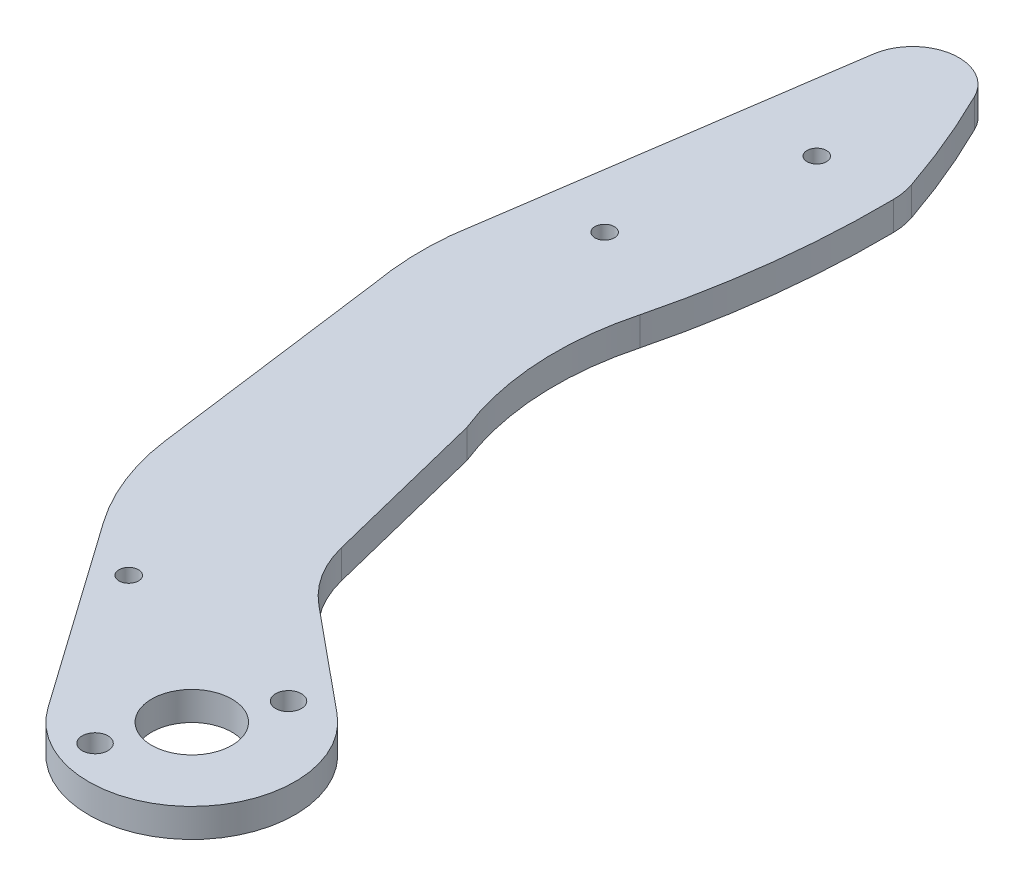
SolidWorks part; units mm, degrees
ref_plane "Front Plane" through (0, 0, 0) normal (0, 0, 1) x (1, 0, 0)
ref_plane "Top Plane" through (0, 0, 0) normal (0, 1, 0) x (1, 0, 0)
ref_plane "Right Plane" through (0, 0, 0) normal (1, 0, 0) x (0, 0, -1)
sketch "Sketch1" plane through (0, 0, 0) normal (0, 1, 0) x (1, 0, 0)
  line L42 (11.4465, 13.8917) -> (-6.607, 28.7674)
  line L43 (-13.2989, 39.3817) -> (-20.5302, 68.4972)
  line L44 (-41.4826, 160.3656) -> (-50.9327, 96.0562)
  line L45 (-50.3835, 82.3644) -> (-44.8193, 40.2497)
  line L46 (-37.8507, 22.4331) -> (-14.709, -10.3752)
  arc A148 (-22.4566, 100.5997) -> (-20.5302, 68.4972) centre (26.9938, 87.458) ccw
  arc A149 (-22.4566, 100.5997) -> (-17.768, 140.1479) centre (-171.2572, 138.2924) ccw
  arc A150 (-17.768, 140.1479) -> (-18.4178, 143.9365) centre (-30, 140) ccw
  arc A151 (-18.4178, 143.9365) -> (-26.2563, 162.7822) centre (-163.7532, 94.5401) ccw
  arc A152 (-26.2563, 162.7822) -> (-41.4826, 160.3656) centre (-33.4913, 159.1913) ccw
  arc A153 (-50.9327, 96.0562) -> (-50.3835, 82.3644) centre (0.0072, 91.2427) ccw
  circle A154 centre (0, 0) radius 7
  arc A155 (11.4465, 13.8917) -> (-14.709, -10.3752) centre (0, 0) cw
  arc A156 (-6.607, 28.7674) -> (-13.2989, 39.3817) centre (6.1114, 44.2025) cw
  arc A157 (-44.8193, 40.2497) -> (-37.8507, 22.4331) centre (-5.1639, 45.489) ccw
  circle A158 centre (-27.6733, 16.679) radius 1.7
  point P7 (-11.7063, 32.9691)
  point P11 (-43.529, 30.4833)
  dimension "D3" = 65
  dimension "D4" = 14
  dimension "D5" = 11
  dimension "D8" = 20
  dimension "D10" = 40
  dimension "D11" = 3.4
  dimension "D1" = 140
  dimension "D2" = 30
  dimension "D6" = 50
  dimension "D7" = 30
  dimension "D9" = 30
  dimension "D12" = 5
  dimension "D13" = 30
extrude "Boss-Extrude2" add sketch "Sketch1" along normal blind 5
sketch "Sketch2" plane through (0, 5, 0) normal (0, 1, 0) x (1, 0, 0)
  line L0 (11.4465, 13.8917) -> (-6.607, 28.7674) construction
  point P0 (8.4963, 16.3225)
sketch "Sketch3" plane through (0, 5, 0) normal (0, 1, 0) x (1, 0, 0)
  circle A0 centre (-31, 140) radius 1.7
  circle A1 centre (-38, 110) radius 1.7
  dimension "D1" = 3.4
  dimension "D2" = 3.4
  dimension "D3" = 30
  dimension "D4" = 110
  dimension "D5" = 38
  dimension "D6" = 7
extrude "Cut-Extrude1" cut sketch "Sketch3" against normal up to next
sketch "Sketch4" plane through (0, 5, 0) normal (0, 1, 0) x (1, 0, 0)
  point P0 (5.2512, 11.6184)
  point P1 (-5.2512, -11.6184)
hole_wizard "M4 Clearance Hole1" positions "3DSketch2" profile "Sketch6" hole size "M4" standard "ISO"
sketch3d "3DSketch2"
  point P0 (-5.2512, 5, 11.6184)
  point P2 (5.2512, 5, -11.6184)
sketch "Sketch6" plane through (-5.2512, 5, 11.6184) normal (1, 0, 0) x (0, 0, 1)
  line L0 (0, 0) -> (0, 11.4519)
  line L1 (0, 11.4519) -> (2.25, 10.1)
  line L2 (2.25, 10.1) -> (2.25, 0)
  line L5 (2.25, 0) -> (0, 0)
  line L10 (0, 11.4519) -> (-2.25, 10.1) construction
  line L11 (0, -6.35) -> (0, 107.95) construction
  dimension "Hole Dia." = 4.5
  dimension "Hole Depth" = 10.1
  dimension "Drill Angle" = 118
